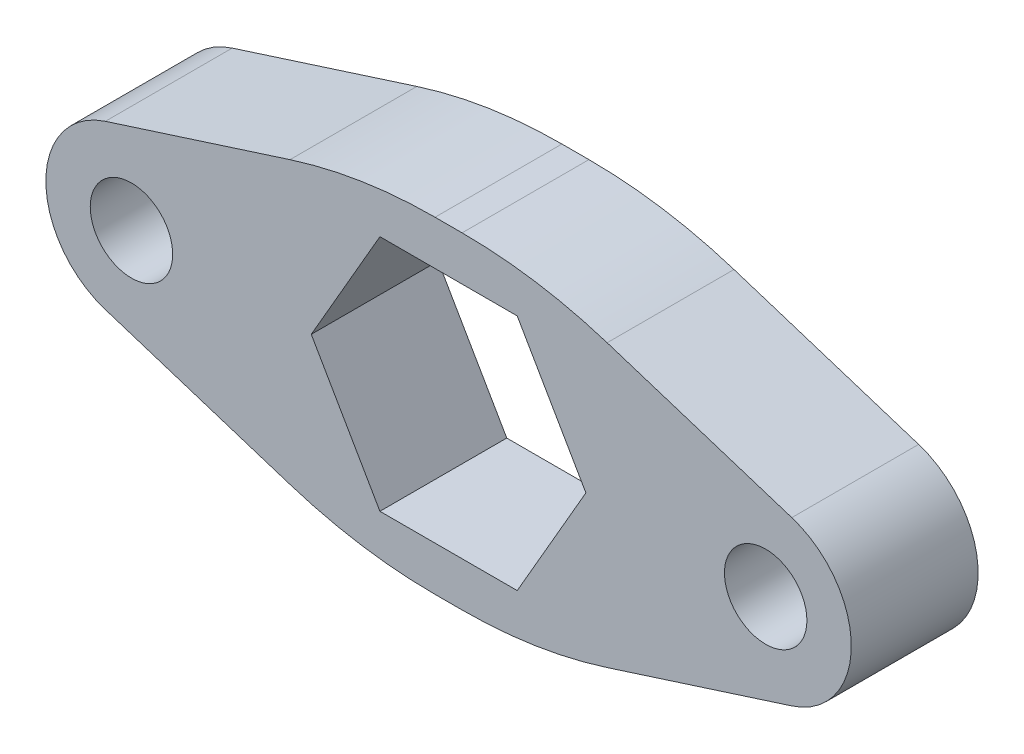
SolidWorks part; units mm, degrees
ref_plane "Front Plane" through (0, 0, 0) normal (0, 0, 1) x (1, 0, 0)
ref_plane "Top Plane" through (0, 0, 0) normal (0, 1, 0) x (1, 0, 0)
ref_plane "Right Plane" through (0, 0, 0) normal (1, 0, 0) x (0, 0, -1)
sketch "Sketch1" plane through (0, 0, 0) normal (0, 0, 1) x (1, 0, 0)
  line L0 (55, 0) -> (-55, 0) construction
  line L1 (10.8232, 2.5714) -> (5, 4.4357)
  line L2 (0.4264, 5.15) -> (-0.4264, 5.15)
  line L3 (0, -55) -> (0, 55) construction
  line L4 (-4.3301, 0) -> (4.3301, 0) construction
  line L5 (2.1651, 3.75) -> (-2.1651, 3.75)
  line L6 (-2.1651, 3.75) -> (-4.3301, 0)
  line L7 (-4.3301, 0) -> (-2.1651, -3.75)
  line L8 (-2.1651, -3.75) -> (2.1651, -3.75)
  line L9 (2.1651, -3.75) -> (4.3301, 0)
  line L10 (4.3301, 0) -> (2.1651, 3.75)
  line L11 (0.4264, -5.15) -> (-0.4264, -5.15)
  line L12 (10.8232, -2.5714) -> (5, -4.4357)
  line L13 (0, 0) -> (0, 3.75) construction
  line L14 (-10.8232, -2.5714) -> (-5, -4.4357)
  line L15 (-10.8232, 2.5714) -> (-5, 4.4357)
  arc A0 (10.8232, -2.5714) -> (10.8232, 2.5714) centre (10, 0) ccw
  arc A1 (5, 4.4357) -> (0.4264, 5.15) centre (0.4264, -9.85) ccw
  circle A2 centre (10, 0) radius 1.3
  circle A3 centre (0, 0) radius 3.75 construction
  arc A4 (5, -4.4357) -> (0.4264, -5.15) centre (0.4264, 9.85) cw
  arc A5 (-5, -4.4357) -> (-0.4264, -5.15) centre (-0.4264, 9.85) ccw
  arc A6 (-10.8232, -2.5714) -> (-10.8232, 2.5714) centre (-10, 0) cw
  arc A7 (-5, 4.4357) -> (-0.4264, 5.15) centre (-0.4264, -9.85) cw
  circle A8 centre (-10, 0) radius 1.3
  point P27 (0, -5.15)
  point P35 (0, 5.15)
  dimension "D1" = 2.6
  dimension "D2" = 1.4
  dimension "D4" = 15
  dimension "D3" = 10
  dimension "D5" = 5
  dimension "D6" = 1.4
  dimension "D7" = 7.5
extrude "Boss-Extrude1" add sketch "Sketch1" along normal blind 4
